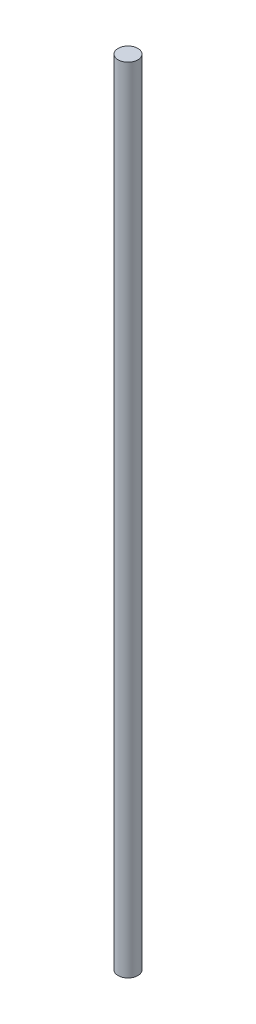
SolidWorks part; units mm, degrees
ref_plane "前视基准面" through (0, 0, 0) normal (0, 0, 1) x (1, 0, 0)
ref_plane "上视基准面" through (0, 0, 0) normal (0, 1, 0) x (1, 0, 0)
ref_plane "右视基准面" through (0, 0, 0) normal (1, 0, 0) x (0, 0, -1)
other "Configuration Table"
sketch "草图1" plane through (0, 0, 0) normal (0, 1, 0) x (1, 0, 0)
  circle A0 centre (0, 0) radius 2
  dimension "D1" = 4
extrude "凸台-拉伸1" add sketch "草图1" along normal blind 160
